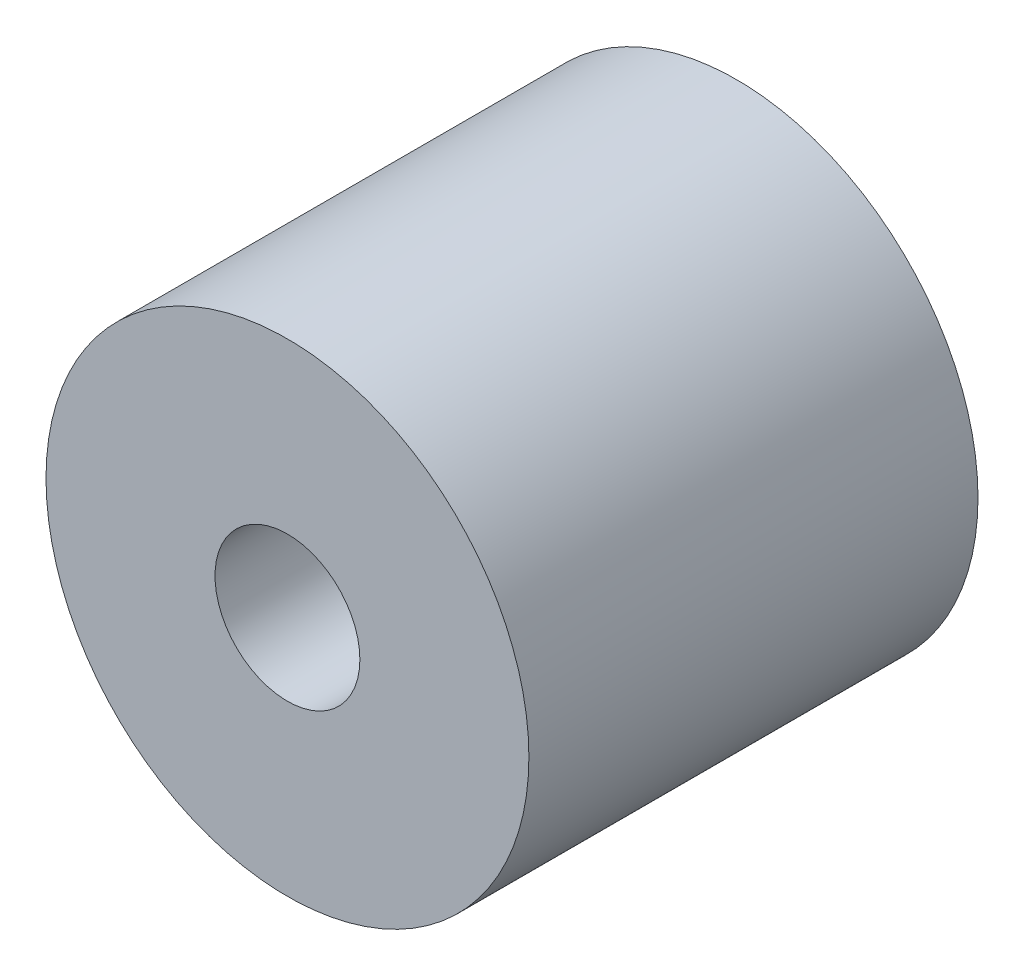
SolidWorks part; units mm, degrees
ref_plane "Ebene vorne" through (0, 0, 0) normal (0, 0, 1) x (1, 0, 0)
ref_plane "Ebene oben" through (0, 0, 0) normal (0, 1, 0) x (1, 0, 0)
ref_plane "Ebene rechts" through (0, 0, 0) normal (1, 0, 0) x (0, 0, -1)
sketch "Skizze1" plane through (0, 0, 0) normal (0, 0, 1) x (1, 0, 0)
  circle A0 centre (0, 0) radius 5
  dimension "D1" = 10
extrude "Aufsatz-Linear austragen1" add sketch "Skizze1" along normal blind 9.3
sketch "Skizze2" plane through (0, 0, 9.3) normal (0, 0, 1) x (1, 0, 0)
  circle A0 centre (0, 0) radius 1.5
  dimension "D1" = 3
extrude "Schnitt-Linear austragen1" cut sketch "Skizze2" against normal through all both and the other way through all
sketch "Skizze3" plane through (0, 0, 0) normal (0, 1, 0) x (1, 0, 0)
  line L0 (5, 0) -> (-5, 0) construction
  circle A0 centre (0, -2) radius 0.5
  dimension "D1" = 1
  dimension "D2" = 2
hole_wizard "Ø1.0 (1) Durchmesser Bohrung3" positions "Skizze7" profile "Skizze8" hole size "Ø1.0" standard "DIN"
sketch "Skizze7" plane through (0, 0, 0) normal (0, 1, 0) x (1, 0, 0)
  line L0 (1.5, 0) -> (-1.5, 0) construction
  point P0 (0, -2)
  dimension "D1" = 2
sketch "Skizze8" plane through (0, 0, 2) normal (1, 0, 0) x (0, 0, -1)
  line L0 (0, 0) -> (0, 4.3004)
  line L1 (0, 4.3004) -> (0.5, 4)
  line L2 (0.5, 4) -> (0.5, 0)
  line L5 (0.5, 0) -> (0, 0)
  line L10 (0, 4.3004) -> (-0.5, 4) construction
  line L11 (0, -6.35) -> (0, 107.95) construction
  dimension "Bohrerdurchmesser" = 1
  dimension "Bohrungstiefe" = 4
  dimension "Spitzenwinkel" = 118
sketch "Skizze9" plane through (0, 0, 0) normal (0, 1, 0) x (1, 0, 0)
  circle A0 centre (0, -2) radius 0.5
extrude "Schnitt-Linear austragen2" cut sketch "Skizze9" against normal blind 10
